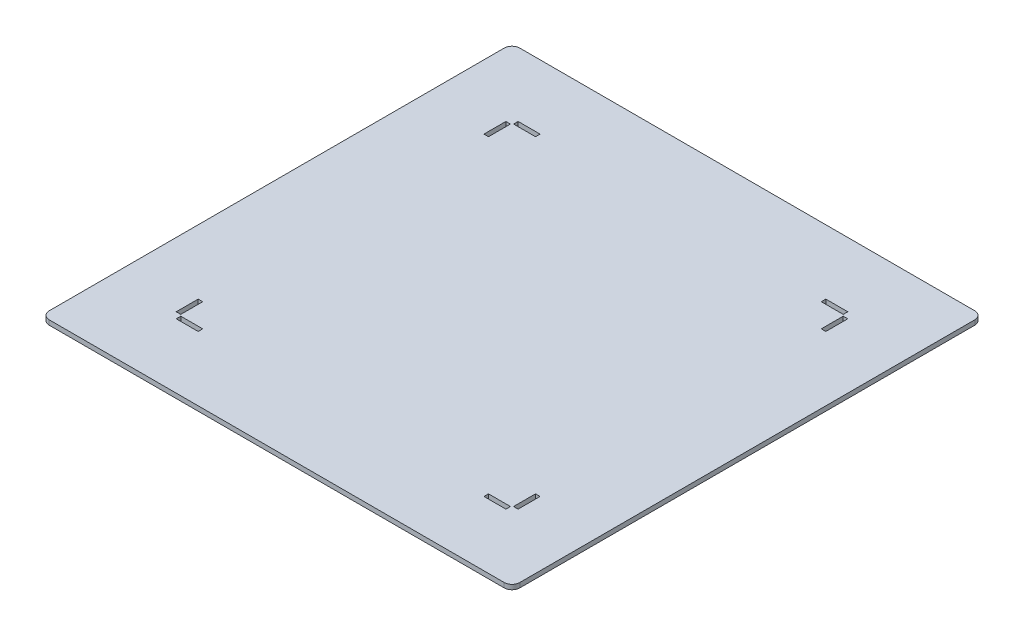
SolidWorks part; units mm, degrees
ref_plane "Front Plane" through (0, 0, 0) normal (0, 0, 1) x (1, 0, 0)
ref_plane "Top Plane" through (0, 0, 0) normal (0, 1, 0) x (1, 0, 0)
ref_plane "Right Plane" through (0, 0, 0) normal (1, 0, 0) x (0, 0, -1)
sketch "Sketch1" plane through (0, 0, 0) normal (0, 1, 0) x (1, 0, 0)
  line L0 (-150, -150) -> (150, 150) construction
  line L1 (-150, 150) -> (150, 150)
  line L2 (-150, 150) -> (-150, -150)
  line L3 (-150, -150) -> (150, -150)
  line L4 (150, 150) -> (150, -150)
  line L5 (-150, 150) -> (150, -150) construction
  line L6 (-10.6066, 10.6066) -> (91.066, 106.066) construction
  line L7 (91.066, 106.066) -> (106.066, 106.066) construction
  line L8 (106.066, 106.066) -> (106.066, 91.066) construction
  line L9 (106.066, 91.066) -> (10.6066, -10.6066) construction
  line L10 (108.966, -91.066) -> (108.966, -105.066)
  line L11 (91.066, 108.966) -> (105.066, 108.966)
  line L12 (91.066, 108.966) -> (91.066, 106.066)
  line L13 (91.066, 106.066) -> (105.066, 106.066)
  line L14 (105.066, 108.966) -> (105.066, 106.066)
  line L15 (106.066, 105.066) -> (108.966, 105.066)
  line L16 (106.066, 105.066) -> (106.066, 91.066)
  line L17 (106.066, 91.066) -> (108.966, 91.066)
  line L18 (108.966, 105.066) -> (108.966, 91.066)
  line L19 (108.966, -91.066) -> (106.066, -91.066)
  line L20 (106.066, -91.066) -> (106.066, -105.066)
  line L21 (108.966, -105.066) -> (106.066, -105.066)
  line L22 (105.066, -106.066) -> (105.066, -108.966)
  line L23 (105.066, -106.066) -> (91.066, -106.066)
  line L24 (91.066, -106.066) -> (91.066, -108.966)
  line L25 (105.066, -108.966) -> (91.066, -108.966)
  line L26 (-91.066, -108.966) -> (-105.066, -108.966)
  line L27 (-91.066, -108.966) -> (-91.066, -106.066)
  line L28 (-91.066, -106.066) -> (-105.066, -106.066)
  line L29 (-105.066, -108.966) -> (-105.066, -106.066)
  line L30 (-106.066, -105.066) -> (-108.966, -105.066)
  line L31 (-106.066, -105.066) -> (-106.066, -91.066)
  line L32 (-106.066, -91.066) -> (-108.966, -91.066)
  line L33 (-108.966, -105.066) -> (-108.966, -91.066)
  line L34 (-108.966, 91.066) -> (-108.966, 105.066)
  line L35 (-108.966, 91.066) -> (-106.066, 91.066)
  line L36 (-106.066, 91.066) -> (-106.066, 105.066)
  line L37 (-108.966, 105.066) -> (-106.066, 105.066)
  line L38 (-105.066, 106.066) -> (-105.066, 108.966)
  line L39 (-105.066, 106.066) -> (-91.066, 106.066)
  line L40 (-91.066, 106.066) -> (-91.066, 108.966)
  line L41 (-105.066, 108.966) -> (-91.066, 108.966)
  point P4 (0, 0)
  point P17 (0, 0)
  point P45 (0, 0)
  dimension "D3" = 150
  dimension "D6" = 15
  dimension "D7" = 15
  dimension "D1" = 300
  dimension "D2" = 300
  dimension "D4" = 15
  dimension "D5" = 15
  dimension "D8" = 14
  dimension "D9" = 2.9
  dimension "D10" = 14
  dimension "D11" = 2.9
  dimension "D12" = 4
extrude "Boss-Extrude1" add sketch "Sketch1" along normal blind 3
fillet "Fillet1" radius 5 4 edges at (150, 1.5, 150) (150, 1.5, -150) (-150, 1.5, -150) (-150, 1.5, 150)
